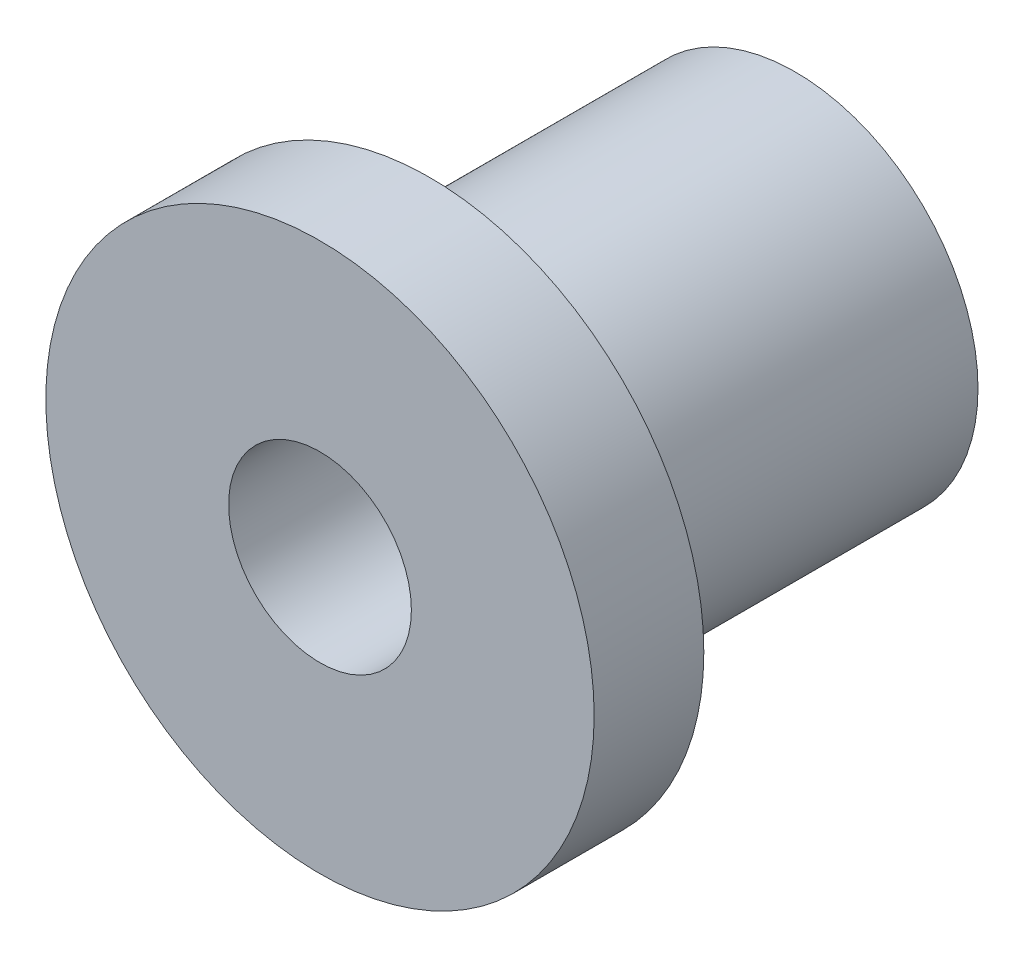
SolidWorks part; units mm, degrees
ref_plane "Alzado" through (0, 0, 0) normal (0, 0, 1) x (1, 0, 0)
ref_plane "Planta" through (0, 0, 0) normal (0, 1, 0) x (1, 0, 0)
ref_plane "Vista lateral" through (0, 0, 0) normal (1, 0, 0) x (0, 0, -1)
sketch "Croquis1" plane through (0, 0, 0) normal (0, 0, 1) x (1, 0, 0)
  circle A0 centre (0, 0) radius 5
  circle A1 centre (0, 0) radius 2.5
extrude "Saliente-Extruir1" add sketch "Croquis1" along normal blind 10
sketch "Croquis2" plane through (0, 0, 10) normal (0, 0, 1) x (1, 0, 0)
  circle A0 centre (0, 0) radius 2.5
  circle A1 centre (0, 0) radius 7.5
extrude "Saliente-Extruir2" add sketch "Croquis2" along normal blind 3
